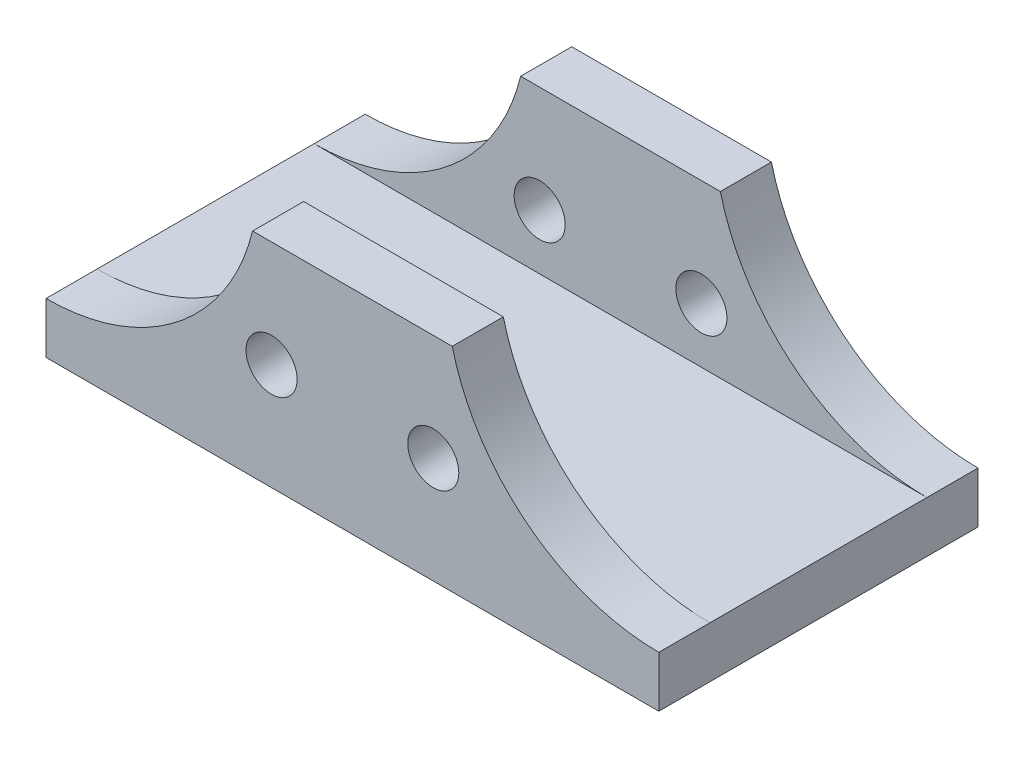
SolidWorks part; units mm, degrees
ref_plane "Front Plane" through (0, 0, 0) normal (0, 0, 1) x (1, 0, 0)
ref_plane "Top Plane" through (0, 0, 0) normal (0, 1, 0) x (1, 0, 0)
ref_plane "Right Plane" through (0, 0, 0) normal (1, 0, 0) x (0, 0, -1)
sketch "Sketch1" plane through (0, 0, 0) normal (0, 0, 1) x (1, 0, 0)
  line L1 (-72, 25) -> (72, 25)
  line L2 (-72, 25) -> (-72, -25)
  line L3 (-72, -25) -> (72, -25)
  line L4 (72, 25) -> (72, -25)
  line L5 (-72, 25) -> (72, -25) construction
  line L6 (-72, -25) -> (72, 25) construction
  point P0 (0, 0)
  dimension "D1" = 144
  dimension "D2" = 50
extrude "Boss-Extrude1" add sketch "Sketch1" along normal mid plane 75
sketch "Sketch2" plane through (0, 0, 37.5) normal (0, 0, 1) x (1, 0, 0)
  line L0 (72, 25) -> (-72, 25) construction
  line L1 (-72, 25) -> (-72, -25) construction
  line L2 (-23.4614, 25) -> (-72, 25)
  line L3 (-72, 25) -> (-72, -13)
  line L4 (-72, -25) -> (72, -25) construction
  line L5 (0, -27.5) -> (0, 27.5) construction
  line L6 (72, 25) -> (72, -13)
  line L7 (23.4614, 25) -> (72, 25)
  arc A0 (-72, -13) -> (-23.4614, 25) centre (-72, 37) ccw
  arc A1 (72, -13) -> (23.4614, 25) centre (72, 37) cw
  point P7 (0, 0)
  point P10 (-77.8409, 36.0499)
  dimension "D1" = 50
  dimension "D2" = 12
extrude "Cut-Extrude1" cut sketch "Sketch2" against normal blind 75
sketch "Sketch3" plane through (0, 25, 0) normal (0, 1, 0) x (1, 0, 0)
  line L0 (72, 37.5) -> (72, -37.5) construction
  line L1 (-72, 25.5) -> (72, 25.5)
  line L2 (-72, 25.5) -> (-72, -25.5)
  line L3 (-72, -25.5) -> (72, -25.5)
  line L4 (72, 25.5) -> (72, -25.5)
  line L5 (-72, 25.5) -> (72, -25.5) construction
  line L6 (-72, -25.5) -> (72, 25.5) construction
  line L7 (-72, -37.5) -> (-23.4614, -37.5) construction
  point P0 (0, 0)
  dimension "D1" = 12
extrude "Cut-Extrude2" cut sketch "Sketch3" against normal blind 38
hole_wizard "Hole1" positions "Sketch4" profile "Sketch5" legacy end condition through all
sketch "Sketch4" plane through (0, 0, 37.5) normal (0, 0, 1) x (1, 0, 0)
  point P0 (19, 0)
  point P2 (-19, 0)
  dimension "D1" = 38
  dimension "D2" = 19
sketch "Sketch5" plane through (19, 0, 37.5) normal (1, 0, 0) x (0, -1, 0)
  line L0 (0, 0) -> (0, 75)
  line L1 (0, 75) -> (6, 75)
  line L2 (6, 75) -> (6, 0)
  line L3 (6, 0) -> (0, 0)
  line L4 (0, 110) -> (0, -10) construction
  dimension "Diameter" = 12
  dimension "Depth" = 75
